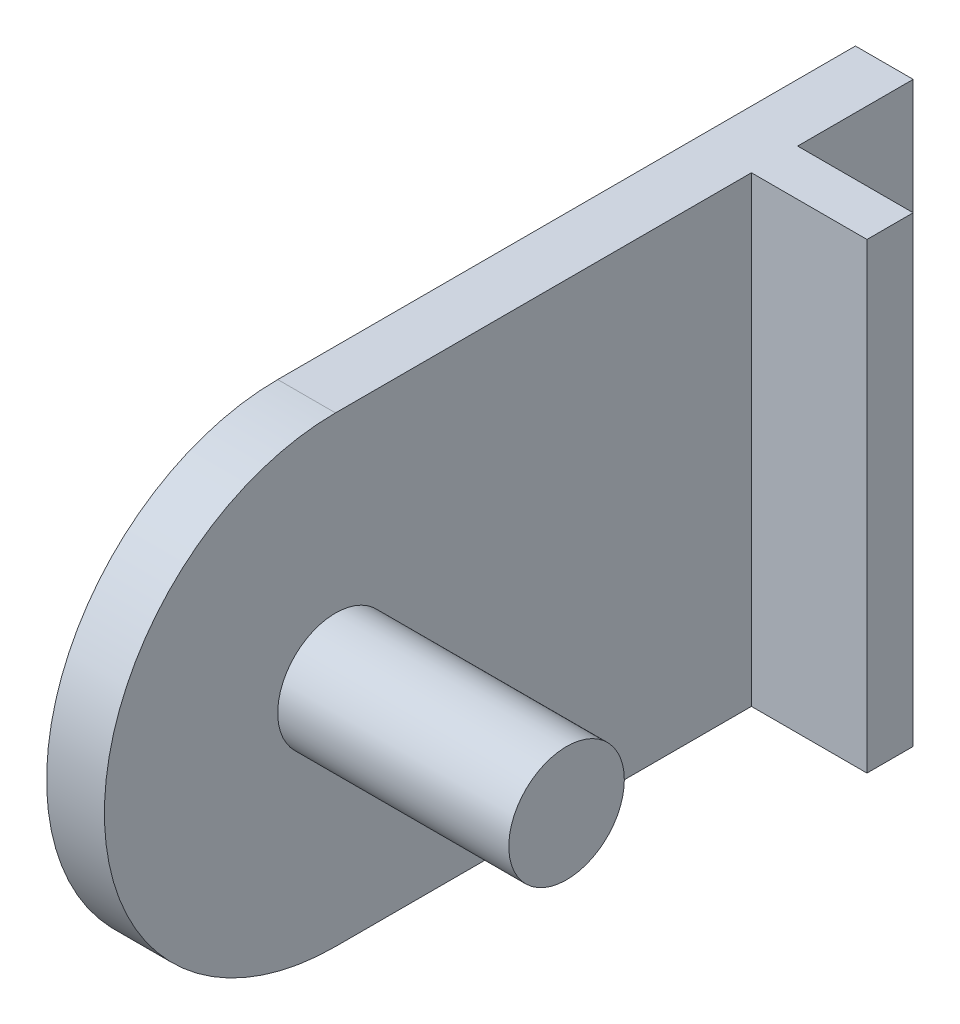
SolidWorks part; units mm, degrees
ref_plane "Front Plane" through (0, 0, 0) normal (1, 0, 0) x (0, 1, 0)
ref_plane "Top Plane" through (0, 0, 0) normal (0, 0, 1) x (0, 1, 0)
ref_plane "Right Plane" through (0, 0, 0) normal (0, 1, 0) x (-1, 0, 0)
sketch "Sketch1" plane through (0, 0, 0) normal (1, 0, 0) x (0, 1, 0)
  line L2 (20, 0) -> (20, -50)
  line L3 (20, -50) -> (-20, -50)
  line L4 (-20, 0) -> (-20, -50)
  line L5 (7.4278, 18.5695) -> (-20, -50) construction
  line L6 (20, -50) -> (-7.4278, 18.5695) construction
  arc A0 (20, 0) -> (-20, 0) centre (0, 0) ccw
  dimension "D1" = 40
  dimension "D2" = 50
extrude "Boss-Extrude1" add sketch "Sketch1" along normal blind 5
sketch "Sketch2" plane through (5, 0, 0) normal (1, 0, 0) x (0, 1, 0)
  line L0 (-20, -50) -> (-20, -40)
  line L1 (-20, 0) -> (-20, -50) construction
  line L2 (20, -50) -> (20, 0) construction
  line L3 (-20, -40) -> (20, -40)
  line L4 (-20, -40) -> (-20, -36)
  line L5 (-20, -36) -> (20, -36)
  line L6 (20, -40) -> (20, -36)
  dimension "D1" = 10
  dimension "D2" = 4
extrude "Boss-Extrude2" add sketch "Sketch2" along normal blind 10 contours L4 L3 L6 L5
sketch "Sketch3" plane through (5, 0, 0) normal (1, 0, 0) x (0, 1, 0)
  circle A0 centre (0, 0) radius 5
  dimension "D1" = 10
extrude "Boss-Extrude3" add sketch "Sketch3" along normal blind 20
